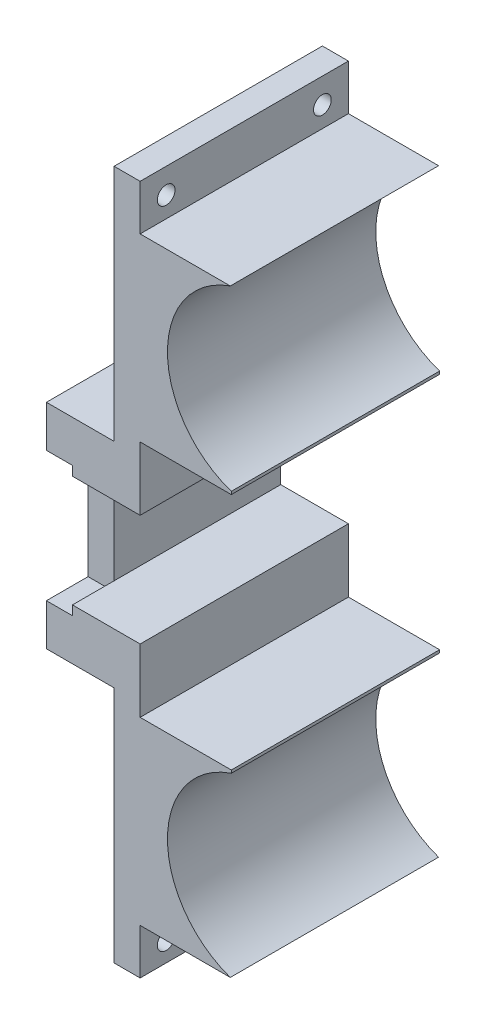
SolidWorks part; units mm, degrees
ref_plane "Płaszczyzna przednia" through (0, 0, 0) normal (0, 0, 1) x (1, 0, 0)
ref_plane "Płaszczyzna górna" through (0, 0, 0) normal (0, 1, 0) x (1, 0, 0)
ref_plane "Płaszczyzna prawa" through (0, 0, 0) normal (1, 0, 0) x (0, 0, -1)
sketch "Sketch1" plane through (0, 0, 0) normal (0, 0, 1) x (1, 0, 0)
  line L0 (0, 0) -> (0, -20.5)
  line L1 (0, -20.5) -> (13, -20.5)
  line L2 (13, -20.5) -> (13, -66.25)
  line L3 (13, -66.25) -> (18, -66.25)
  line L4 (18, -66.25) -> (18, -57.5)
  line L5 (18, -57.5) -> (35.3144, -57.5)
  line L7 (37.5083, -22.9) -> (18, -22.9)
  line L8 (18, -22.9) -> (18, -10.7)
  line L9 (18, -10.7) -> (5, -10.7)
  line L10 (5, -10.7) -> (5, 0)
  line L11 (5, 0) -> (0, 0)
  line L12 (35.5083, -22.9) -> (35.5083, -23.4471)
  line L13 (35.5083, -57.5665) -> (35.5083, -57.5)
  arc A0 (37.5083, -22.9) -> (35.3144, -57.5) centre (41.25, -40.5068) ccw
  dimension "D10" = 19.5083
  dimension "D5" = 18
  dimension "D1" = 10.7
  dimension "D2" = 13
  dimension "D3" = 12.2
  dimension "D4" = 28.25
  dimension "D6" = 5
  dimension "D7" = 5
  dimension "D8" = 20.5
  dimension "D9" = 45.75
  dimension "D11" = 34.6
  dimension "D12" = 2
extrude "Boss-Extrude1" add sketch "Sketch1" along normal blind 40 contours A0 L12 L7 L8 L9 L10 L11 L0 L1 L2 L3 L4 L5 L13
mirror "Mirror1" about plane through (0, 0, 0) normal (0, 1, 0) of "Boss-Extrude1"
sketch "Sketch3" plane through (13, 0, 0) normal (-1, 0, 0) x (0, 0, 1)
  point P0 (35, -62.4818)
  point P1 (5, -62.4818)
  point P3 (35, 61.4682)
  point P5 (5, 61.4682)
hole_wizard "M3 Clearance Hole1" positions "Sketch3" profile "Sketch5" hole size "M3" standard "DIN" end condition up to next
sketch "Sketch5" plane through (13, -62.4818, 35) normal (0, 1, 0) x (0, 0, 1)
  line L0 (0, 0) -> (0, 5)
  line L1 (0, 5) -> (1.7, 5)
  line L2 (1.7, 5) -> (1.7, 0)
  line L5 (1.7, 0) -> (0, 0)
  line L11 (0, -6.35) -> (0, 107.95) construction
  dimension "Thru Hole Dia." = 3.4
  dimension "Thru Hole Depth" = 5
sketch "Sketch6" plane through (0, 0, 40) normal (0, 0, -1) x (-1, 0, 0)
  line L0 (-5, -10.7) -> (-5, 10.7) construction
  line L1 (-5, 12.5) -> (0, 12.5)
  line L2 (-5, 12.5) -> (-5, -12.5)
  line L3 (-5, -12.5) -> (0, -12.5)
  line L4 (0, 12.5) -> (0, -12.5)
  line L5 (-2.5, -12.5) -> (-2.5, 12.5) construction
  line L6 (-5, 0) -> (0, 0) construction
  line L7 (0, 20.5) -> (0, -20.5) construction
  point P164 (-2.5, 0)
  dimension "D1" = 25
extrude "Cut-Extrude1" cut sketch "Sketch6" along normal blind 8
sketch "Sketch7" plane through (0, 0, 0) normal (-1, 0, 0) x (0, 0, 1)
  line L0 (40, -20.5) -> (0, -20.5) construction
  line L1 (0, 20.5) -> (40, 20.5)
  line L2 (0, 20.5) -> (0, -20.5)
  line L3 (0, -20.5) -> (40, -20.5)
  line L4 (40, 20.5) -> (40, -20.5)
  line L5 (20, -20.5) -> (20, 20.5) construction
  line L6 (0, 0) -> (40, 0) construction
  point P204 (20, 0)
hole_wizard "M3 Clearance Hole2" positions "Sketch7" profile "Sketch8" hole size "M3" standard "DIN" end condition up to next
sketch "Sketch8" plane through (0, 0, 20) normal (0, 1, 0) x (0, 0, 1)
  line L0 (0, 0) -> (0, 5)
  line L1 (0, 5) -> (1.7, 5)
  line L2 (1.7, 5) -> (1.7, 0)
  line L5 (1.7, 0) -> (0, 0)
  line L11 (0, -6.35) -> (0, 107.95) construction
  dimension "Thru Hole Dia." = 3.4
  dimension "Thru Hole Depth" = 5
